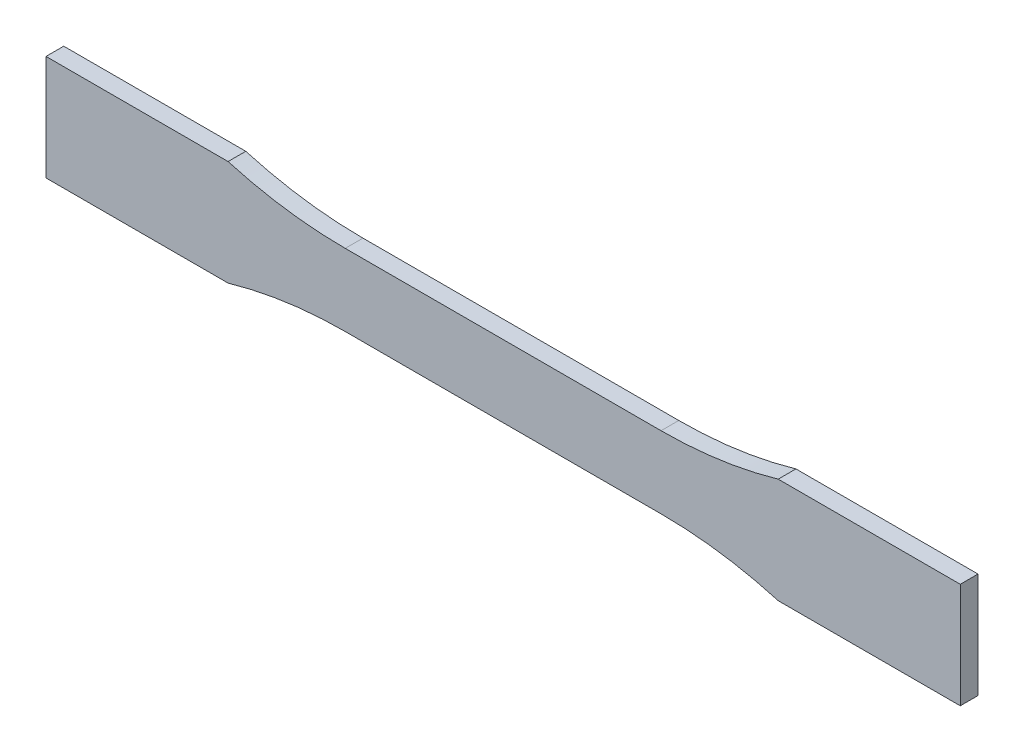
SolidWorks part; units mm, degrees
ref_plane "Front Plane" through (0, 0, 0) normal (0, 0, 1) x (1, 0, 0)
ref_plane "Top Plane" through (0, 0, 0) normal (0, 1, 0) x (1, 0, 0)
ref_plane "Right Plane" through (0, 0, 0) normal (1, 0, 0) x (0, 0, -1)
sketch "Sketch1" plane through (0, 0, 0) normal (0, 0, 1) x (1, 0, 0)
  line L0 (-82.5, 9.5) -> (-82.5, -9.5)
  line L1 (-82.5, -9.5) -> (-49.6424, -9.5)
  line L2 (-82.5, 9.5) -> (-49.6424, 9.5)
  line L3 (49.6424, 9.5) -> (82.5, 9.5)
  line L4 (82.5, 9.5) -> (82.5, -9.5)
  line L5 (82.5, -9.5) -> (49.6424, -9.5)
  line L6 (-28.5, -6.5) -> (28.5, -6.5)
  line L7 (-28.5, 6.5) -> (28.5, 6.5)
  line L11 (0, -44.7868) -> (0, 44.7868) construction
  line L12 (-57.5, 19.8545) -> (-57.5, -21.6) construction
  line L13 (57.5, 19.8545) -> (57.5, -21.6) construction
  line L14 (-25, 13.3091) -> (-25, -10) construction
  line L15 (25, 13.3091) -> (25, -10) construction
  line L17 (55, 0) -> (-55, 0) construction
  arc A1 (28.5, 6.5) -> (49.6424, 9.5) centre (28.5, 82.5) ccw
  arc A2 (28.5, -6.5) -> (49.6424, -9.5) centre (28.5, -82.5) cw
  arc A3 (-28.5, -6.5) -> (-49.6424, -9.5) centre (-28.5, -82.5) ccw
  arc A4 (-28.5, 6.5) -> (-49.6424, 9.5) centre (-28.5, 82.5) cw
  point P28 (0, 0)
  point P29 (0, 0)
  dimension "D7" = 76
  dimension "D1" = 19
  dimension "D3" = 13
  dimension "D5" = 57
  dimension "D6" = 28.5
  dimension "D8" = 165
  dimension "D9" = 115
  dimension "D10" = 57.5
  dimension "D11" = 50
  dimension "D12" = 25
  dimension "D2" = 6.5
  dimension "D4" = 9.5
extrude "Boss-Extrude1" add sketch "Sketch1" along normal mid plane 3.2
equation "\"b2\"=19"
equation "\"D1@Sketch1\"=\"b2\""
equation "\"b1\"=13"
equation "\"D3@Sketch1\"=\"b1\""
equation "\"l1\"=57"
equation "\"D5@Sketch1\"=\"l1\""
equation "\"D6@Sketch1\"=\"l1\"/2"
equation "\"R\"=76"
equation "\"D7@Sketch1\"=\"R\""
equation "\"L\"=115"
equation "\"D9@Sketch1\"=\"L\""
equation "\"D10@Sketch1\"=\"L\"/2"
equation "\"L0\"=50"
equation "\"D11@Sketch1\"=\"L0\""
equation "\"D12@Sketch1\"=\"L0\"/2"
equation "\"h\"=3.2"
equation "\"D1@Boss-Extrude1\"=\"h\""
equation "\"D2@Sketch1\"=\"b1\"/2"
equation "\"D4@Sketch1\"=\"b2\"/2"
